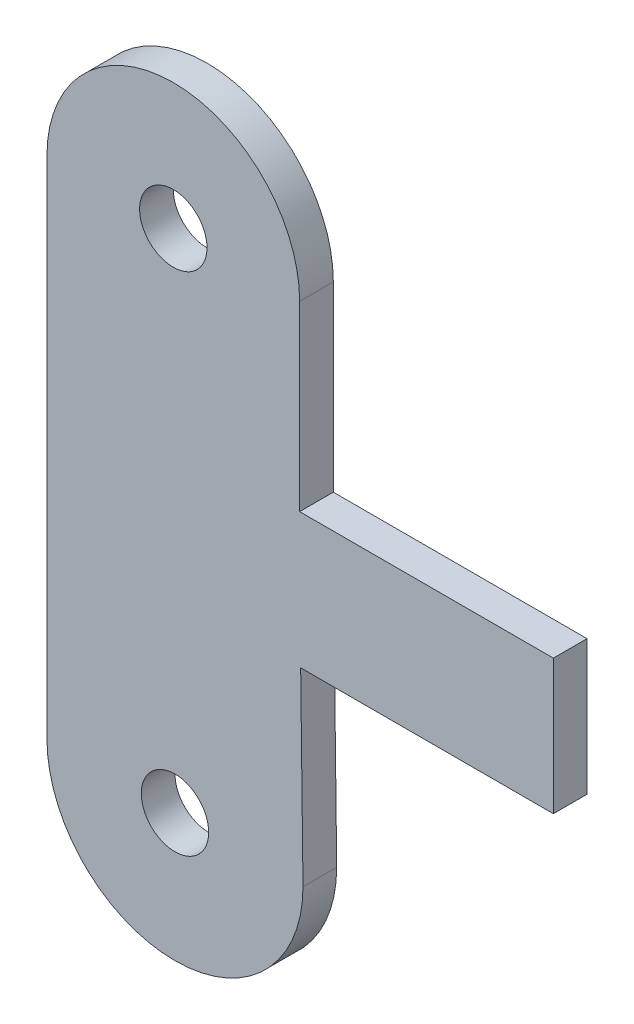
SolidWorks part; units mm, degrees
ref_plane "Front Plane" through (0, 0, 0) normal (0, 0, 1) x (1, 0, 0)
ref_plane "Top Plane" through (0, 0, 0) normal (0, 1, 0) x (1, 0, 0)
ref_plane "Right Plane" through (0, 0, 0) normal (1, 0, 0) x (0, 0, -1)
sketch "Sketch1" plane through (0, 0, 0) normal (0, 0, 1) x (1, 0, 0)
  line L0 (10.0884, 4.4751) -> (10.2271, -6.7132)
  line L1 (-4.9729, 23.2868) -> (-4.9729, -6.7132)
  line L4 (10.0271, 23.2868) -> (10.0271, 12.4751)
  line L5 (10.0271, 12.4751) -> (25.0884, 12.4751)
  line L7 (10.0884, 4.4751) -> (25.0884, 4.4751)
  line L8 (25.0884, 12.4751) -> (25.0884, 4.4751)
  arc A0 (10.0271, 23.2868) -> (-4.9729, 23.2868) centre (2.5271, 23.2868) ccw
  circle A1 centre (2.5271, 23.2868) radius 2
  circle A2 centre (2.6271, -6.7132) radius 2
  arc A3 (-4.9729, -6.7132) -> (10.2247, -6.5249) centre (2.6271, -6.7132) ccw
  point P10 (10.0271, 23.2868)
  dimension "D1" = 15
  dimension "D6" = 4
  dimension "D7" = 4
  dimension "D2" = 11
  dimension "D3" = 30
  dimension "D4" = 8
  dimension "D5" = 15
extrude "Boss-Extrude1" add sketch "Sketch1" along normal blind 2 contours L1 A3 L0 L7 L8 L5 L4 A0 A1 A2
